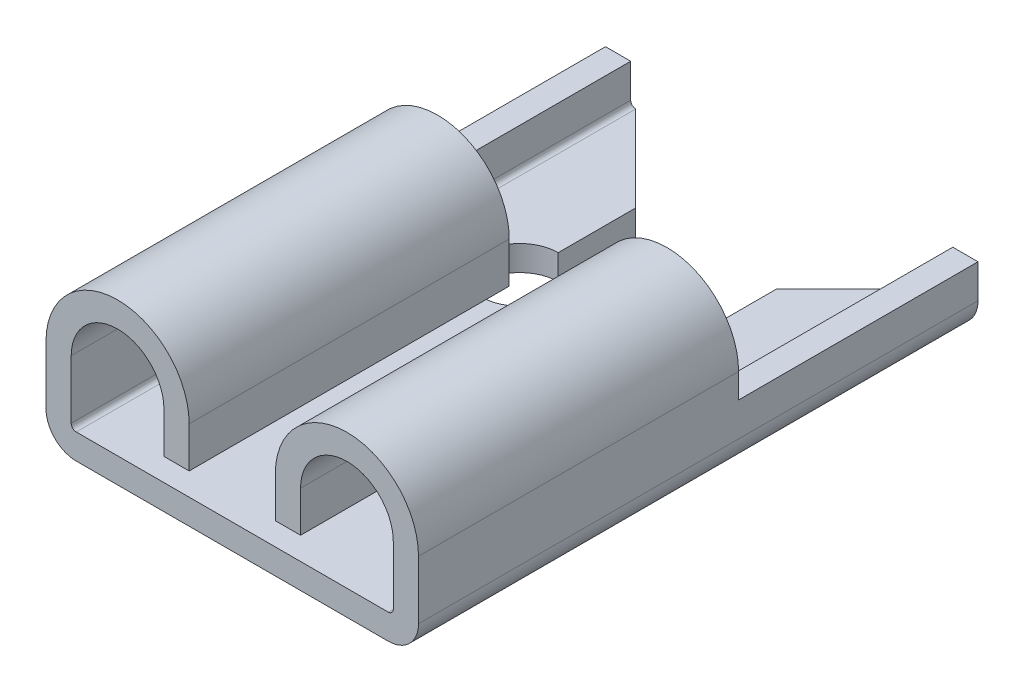
SolidWorks part; units mm, degrees
material "Duranickel(R) 301"
ref_plane "Front Plane" through (0, 0, 0) normal (0, 0, 1) x (1, 0, 0)
ref_plane "Top Plane" through (0, 0, 0) normal (0, 1, 0) x (1, 0, 0)
ref_plane "Right Plane" through (0, 0, 0) normal (1, 0, 0) x (0, 0, -1)
sketch "Sketch1" plane through (0, 0, 0) normal (0, 0, 1) x (1, 0, 0)
  line L0 (0, 0) -> (-3.095, 0)
  line L1 (-3.695, 0.6) -> (-3.695, 1.76)
  line L2 (-2.275, 3.18) -> (-6.9924, 3.18) construction
  line L3 (-0.855, 1.76) -> (-0.855, 0.95)
  line L4 (-2.275, 3.18) -> (-2.275, 0.5) construction
  line L5 (-1.355, 1.76) -> (-3.195, 1.76) construction
  line L6 (0, 0.5) -> (-3.095, 0.5)
  line L7 (-3.195, 0.6) -> (-3.195, 1.76)
  line L8 (-1.355, 1.76) -> (-1.355, 0.95)
  line L9 (-1.355, 0.95) -> (-0.855, 0.95)
  line L10 (0, 0) -> (0, 8.3351) construction
  line L11 (1.355, 1.76) -> (3.195, 1.76) construction
  line L12 (2.275, 3.18) -> (2.275, 0.5) construction
  line L13 (2.275, 3.18) -> (6.9924, 3.18) construction
  line L14 (1.355, 0.95) -> (0.855, 0.95)
  line L15 (1.355, 1.76) -> (1.355, 0.95)
  line L16 (3.195, 0.6) -> (3.195, 1.76)
  line L17 (0, 0.5) -> (3.095, 0.5)
  line L18 (0.855, 1.76) -> (0.855, 0.95)
  line L19 (3.695, 0.6) -> (3.695, 1.76)
  line L20 (0, 0) -> (3.095, 0)
  arc A0 (-0.855, 1.76) -> (-3.695, 1.76) centre (-2.275, 1.76) ccw
  arc A1 (-3.095, 0) -> (-3.695, 0.6) centre (-3.095, 0.6) cw
  arc A2 (-3.095, 0.5) -> (-3.195, 0.6) centre (-3.095, 0.6) cw
  arc A3 (-1.355, 1.76) -> (-3.195, 1.76) centre (-2.275, 1.76) ccw
  arc A4 (1.355, 1.76) -> (3.195, 1.76) centre (2.275, 1.76) cw
  arc A5 (3.095, 0.5) -> (3.195, 0.6) centre (3.095, 0.6) ccw
  arc A6 (3.095, 0) -> (3.695, 0.6) centre (3.095, 0.6) ccw
  arc A7 (0.855, 1.76) -> (3.695, 1.76) centre (2.275, 1.76) cw
  point P0 (3.695, 0)
  point P14 (-3.695, 0)
  dimension "D3" = 1.42
  dimension "D5" = 0.6
  dimension "D1" = 3.18
  dimension "D2" = 3.695
  dimension "D6" = 0.45
  dimension "D7" = 0.5
extrude "Boss-Extrude1" add sketch "Sketch1" along normal blind 11.1
sketch "Sketch2" plane through (0, 0, 0) normal (0, -1, 0) x (1, 0, 0)
  line L0 (-0.633, 4) -> (0.633, 4)
  line L1 (-3.095, 0) -> (3.095, 0) construction
  line L2 (1.395, 1.7) -> (1.395, 3.238)
  line L3 (3.095, 0) -> (1.395, 1.7)
  line L4 (3.095, 0) -> (3.095, -0.5375)
  line L12 (0, -0.5375) -> (0, 4) construction
  line L13 (-3.095, 0) -> (-3.095, -0.5375)
  line L14 (-3.095, 0) -> (-1.395, 1.7)
  line L15 (-3.095, -0.5375) -> (3.095, -0.5375)
  line L20 (-1.395, 1.7) -> (-1.395, 3.238)
  arc A0 (1.395, 3.238) -> (0.633, 4) centre (1.395, 4) ccw
  arc A3 (-1.395, 3.238) -> (-0.633, 4) centre (-1.395, 4) cw
  dimension "D1" = 0.762
  dimension "D2" = 0.5375
  dimension "D3" = 1.395
  dimension "D4" = 45
  dimension "D5" = 4
extrude "Cut-Extrude1" cut sketch "Sketch2" against normal up to next
sketch "Sketch3" plane through (0, 0, 0) normal (0, 0, -1) x (-1, 0, 0)
  line L0 (-3.695, 0.6) -> (-3.695, 1.76) construction
  line L1 (3.695, 3.3117) -> (-3.695, 3.3117)
  line L2 (3.695, 3.3117) -> (3.695, 1.27)
  line L3 (3.695, 1.27) -> (2.941, 1.27)
  line L4 (-3.695, 3.3117) -> (-3.695, 1.27)
  line L5 (3.695, 1.76) -> (3.695, 0.6) construction
  line L6 (-3.195, 1.76) -> (-3.195, 0.6) construction
  line L7 (2.941, 1.27) -> (2.941, 0.77)
  line L8 (2.941, 0.77) -> (-2.941, 0.77)
  line L9 (-2.941, 0.77) -> (-2.941, 1.27)
  line L10 (-2.941, 1.27) -> (-3.695, 1.27)
  line L14 (3.195, 0.6) -> (3.195, 1.76) construction
  line L15 (1.395, 0) -> (3.095, 0) construction
  dimension "D1" = 0.254
  dimension "D2" = 0.5
  dimension "D3" = 0.254
  dimension "D4" = 1.27
extrude "Cut-Extrude2" cut sketch "Sketch3" against normal blind 4.75
scale "Scale1" [suppressed]
